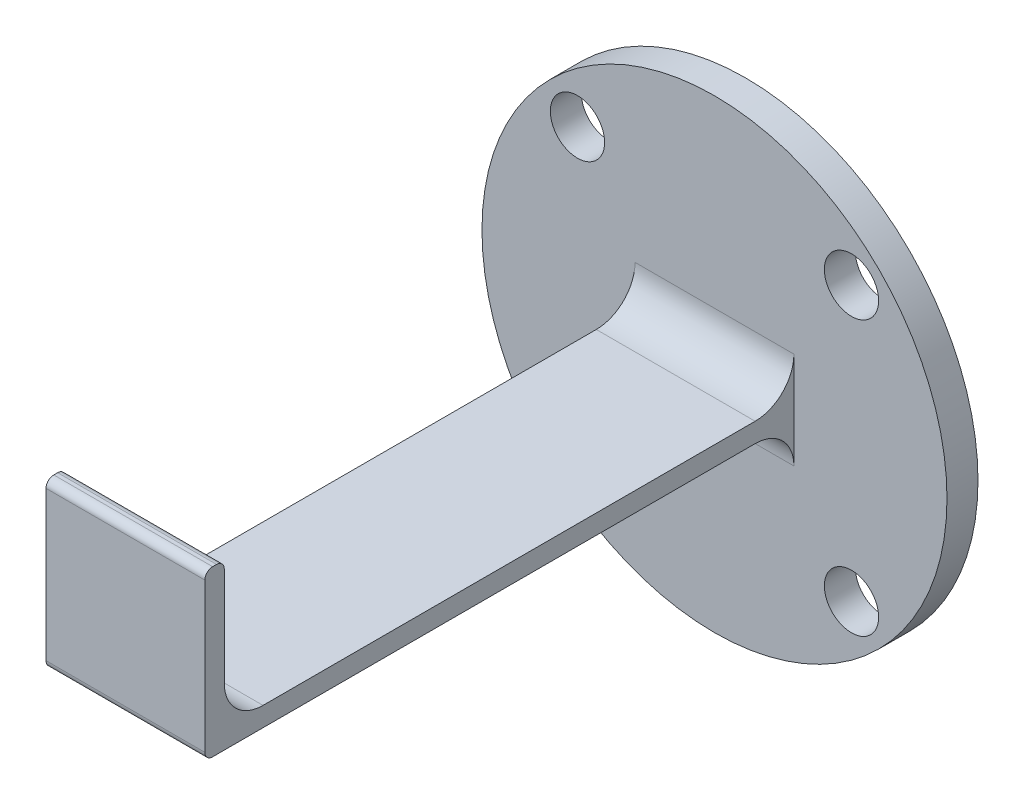
SolidWorks part; units mm, degrees
ref_plane "前视基准面" through (0, 0, 0) normal (0, 0, 1) x (1, 0, 0)
ref_plane "上视基准面" through (0, 0, 0) normal (0, 1, 0) x (1, 0, 0)
ref_plane "右视基准面" through (0, 0, 0) normal (1, 0, 0) x (0, 0, -1)
sketch "草图2" plane through (0, 0, 0) normal (0, 0, 1) x (1, 0, 0)
  circle A0 centre (0, 0) radius 30
  dimension "D1" = 60
extrude "凸台-拉伸1" add sketch "草图2" along normal blind 4 contours A0
sketch "草图3" plane through (0, 0, 4) normal (0, 0, 1) x (1, 0, 0)
  line L2 (0, -55) -> (0, 55) construction
  line L3 (55, 0) -> (-55, 0) construction
  circle A0 centre (-17.6777, 17.6777) radius 3.5
  circle A4 centre (17.6777, 17.6777) radius 3.5
  circle A5 centre (17.6777, -17.6777) radius 3.5
  circle A6 centre (-17.6777, -17.6777) radius 3.5
  dimension "D1" = 25
  dimension "D2" = 7
  dimension "D3" = 35.3553
  dimension "D4" = 35.3553
extrude "切除-拉伸1" cut sketch "草图3" against normal blind 4
sketch "草图4" plane through (0, 0, 0) normal (1, 0, 0) x (0, 0, -1)
  line L0 (-4, 30) -> (-4, -30) construction
  line L1 (-1, -5) -> (-4, -5)
  line L2 (-1, -5) -> (-1, 5)
  line L3 (-1, 5) -> (-4, 5)
  line L4 (-4, -5) -> (-4, 5)
  line L5 (-1, -5) -> (-4, 5) construction
  line L6 (-1, 5) -> (-4, -5) construction
  point P0 (-2.5, 0)
  dimension "D1" = 10
  dimension "D2" = 3
sketch "草图13" plane through (0, 0, 0) normal (0, 1, 0) x (1, 0, 0)
  line L0 (-35, 20) -> (0, 102.9156)
  line L1 (0, -58.2536) -> (0, 58.2536) construction
  line L2 (-35, 20) -> (0, 5.2259)
  line L3 (-47.85, 0) -> (47.85, 0) construction
  dimension "D1" = 35
  dimension "D2" = 90
  dimension "D3" = 0
  dimension "D4" = 20
  dimension "D5" = 90
  dimension "D6" = 0
  dimension "D7" = 82.9156
  dimension "D8" = 67.115
sketch "草图14" plane through (0, 0, 0) normal (0, 0, 1) x (1, 0, 0)
  line L1 (-10.25, -1.25) -> (10.25, -1.25)
  line L2 (-10.25, -1.25) -> (-10.25, 1.25)
  line L3 (-10.25, 1.25) -> (10.25, 1.25)
  line L4 (10.25, -1.25) -> (10.25, 1.25)
  line L5 (-10.25, -1.25) -> (10.25, 1.25) construction
  line L6 (-10.25, 1.25) -> (10.25, -1.25) construction
  point P0 (0, 0)
  dimension "D1" = 20.5
  dimension "D2" = 2.5
extrude "凸台-拉伸2" add sketch "草图14" along normal blind 80
sketch "草图15" plane through (0, 0, 0) normal (0, 1, 0) x (1, 0, 0)
  line L0 (10.25, -80) -> (10.25, -4) construction
  line L1 (-10.25, -80) -> (10.25, -80)
  line L2 (-10.25, -80) -> (-10.25, -77.5)
  line L3 (-10.25, -77.5) -> (10.25, -77.5)
  line L4 (10.25, -80) -> (10.25, -77.5)
  dimension "D1" = 2.5
extrude "凸台-拉伸3" add sketch "草图15" along normal blind 20
sketch "草图16" plane through (0, 0, 80) normal (0, 0, 1) x (1, 0, 0)
  line L0 (10.25, -1.25) -> (10.25, 20) construction
  line L1 (-10.25, 20) -> (10.25, 20)
  line L2 (-10.25, 20) -> (-10.25, 18)
  line L3 (-10.25, 18) -> (10.25, 18)
  line L4 (10.25, 20) -> (10.25, 18)
  dimension "D1" = 2
fillet "圆角1" radius 5 3 edges at (0, -1.25, 4) (0, 1.25, 4) (0, 1.25, 77.5)
fillet "圆角3" radius 1 3 edges at (0, 20, 77.5) (0, 20, 80) (0, -1.25, 80)
